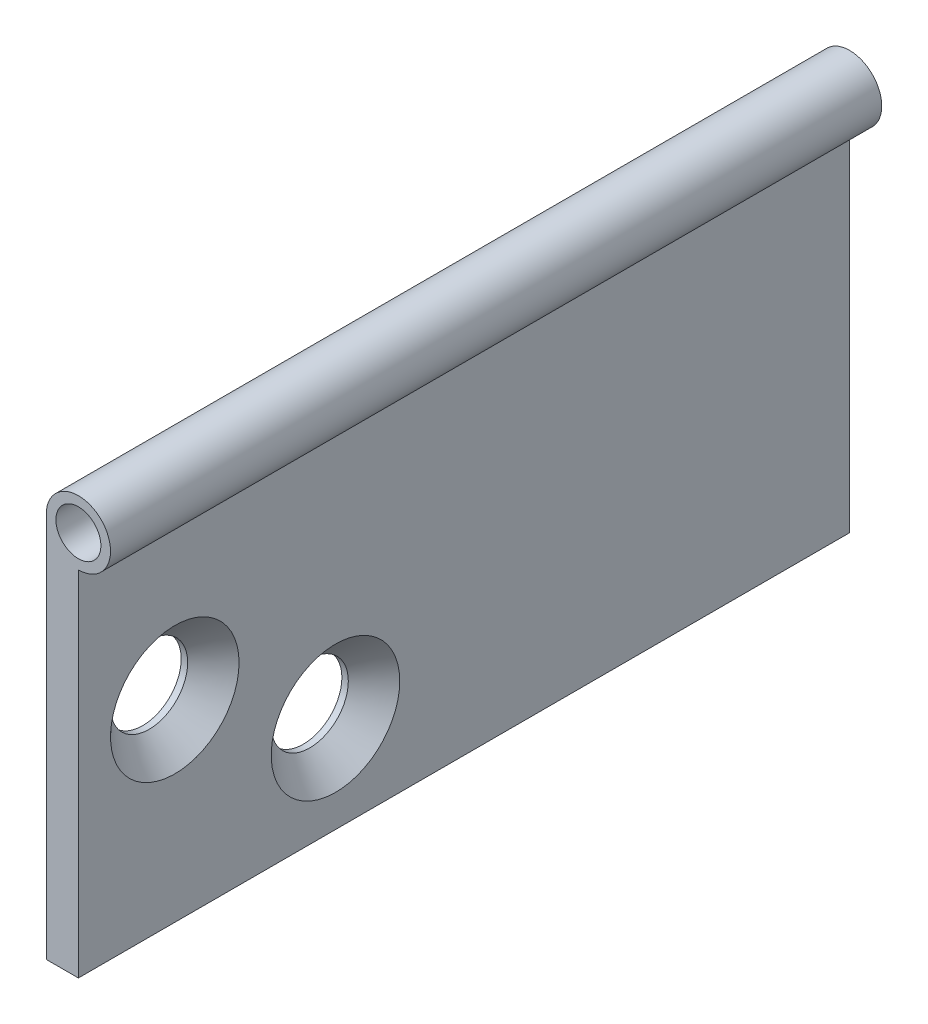
SolidWorks part; units mm, degrees
ref_plane "Спереди" through (0, 0, 0) normal (0, 0, 1) x (1, 0, 0)
ref_plane "Сверху" through (0, 0, 0) normal (0, 1, 0) x (1, 0, 0)
ref_plane "Справа" through (0, 0, 0) normal (1, 0, 0) x (0, 0, -1)
sketch "Эскиз1" plane through (0, 0, 0) normal (0, 0, 1) x (1, 0, 0)
  line L0 (0, 0) -> (0, 60)
  dimension "D1" = 60
extrude "Вытянуть-Тонкостенный2" add sketch "Эскиз1" along normal mid plane 120 thin contours L0
sketch "Эскиз2" plane through (0, 0, 60) normal (0, 0, 1) x (1, 0, 0)
  circle A0 centre (5, 60) radius 5
sweep "По траектории1" add profiles "Эскиз2" path edge at (0, 60, 0)
sketch "Эскиз3" plane through (0, 0, 60) normal (0, 0, 1) x (1, 0, 0)
  circle A0 centre (5, 60) radius 3.5
  dimension "D1" = 7
extrude "Вырез-Вытянуть1" cut sketch "Эскиз3" against normal through all
hole_wizard "Зенковка для  винта с плоской головкой M101" positions "Эскиз7" profile "Эскиз8" countersink size "M10" standard "Ansi Metric" end condition through all
sketch "Эскиз7" plane through (5, 0, 0) normal (1, 0, 0) x (0, 0, -1)
  line L0 (-60, 0) -> (-60, 55) construction
  line L1 (-60, 0) -> (60, 0) construction
  point P0 (-45, 30)
  point P2 (-20, 15)
  point P9 (0, 0)
  dimension "D1" = 15
  dimension "D2" = 30
  dimension "D3" = 40
  dimension "D4" = 15
sketch "Эскиз8" plane through (5, 30, 45) normal (0, 1, 0) x (0, 0, -1)
  line L0 (0, 0) -> (0, 5)
  line L1 (0, 5) -> (6, 5)
  line L2 (6, 5) -> (6, 4)
  line L3 (6, 4) -> (10, 0)
  line L5 (10, 0) -> (0, 0)
  line L6 (-6, 4) -> (-10, 0) construction
  line L11 (0, -6.35) -> (0, 107.95) construction
  dimension "Диаметр сквозного отверстия" = 12
  dimension "Глубина сквозного отверстия" = 5
  dimension "Диаметр передней зенковки" = 20
  dimension "Угол передней зенковки" = 90
equation "\"depth\"= 5"
equation "\"width\"= 60"
equation "\"length\"= 120"
equation "\"D1@Вытянуть-Тонкостенный2\"= \"length\""
equation "\"D1@Эскиз1\"= \"width\""
equation "\"D5@Вытянуть-Тонкостенный2\"= \"depth\""
equation "\"D1@Эскиз3\"= \"depth\" / 5 * 7"
equation "\"D1@Эскиз7\"= \"length\" / 8"
equation "\"D2@Эскиз7\"= \"width\" / 2"
equation "\"D3@Эскиз7\"= \"length\" / 3"
equation "\"D4@Эскиз7\"= \"width\" / 4"
equation "\"D4@Эскиз4\"= \"length\" / 3"
equation "\"D3@Эскиз4\"= \"width\" / 2"
equation "\"D2@Эскиз4\"= \"width\" / 4"
equation "\"D1@Эскиз4\"= \"width\" / 4"
